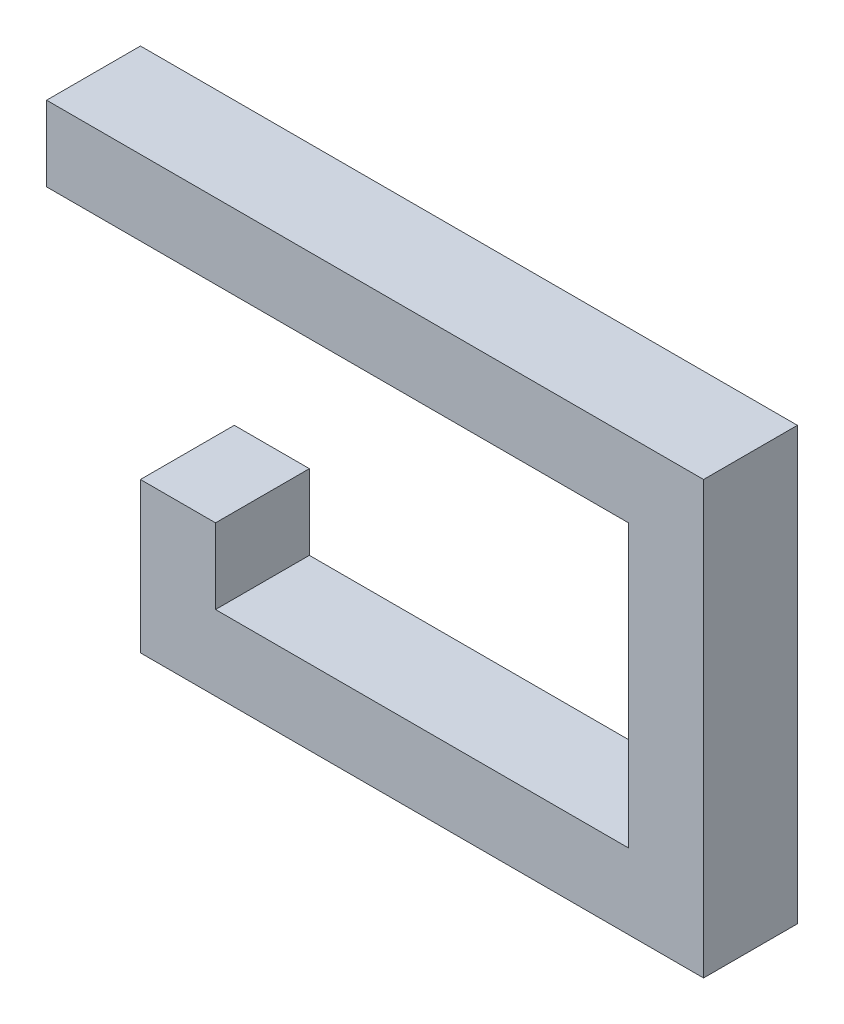
SolidWorks part; units mm, degrees
material "PA Type 6"
ref_plane "Front Plane" through (0, 0, 0) normal (0, 0, 1) x (1, 0, 0)
ref_plane "Top Plane" through (0, 0, 0) normal (0, 1, 0) x (1, 0, 0)
ref_plane "Right Plane" through (0, 0, 0) normal (1, 0, 0) x (0, 0, -1)
sketch "Sketch1" plane through (0, 0, 0) normal (0, 0, 1) x (1, 0, 0)
  line L0 (0, 0) -> (15, 0)
  line L1 (15, 0) -> (15, 11.5)
  line L2 (15, 11.5) -> (-2.5, 11.5)
  line L6 (13, 9.5) -> (13, 2)
  line L8 (0, 2) -> (0, 0)
  line L9 (-2.5, 9.5) -> (13, 9.5)
  line L10 (-2.5, 11.5) -> (-2.5, 9.5)
  line L11 (13, 2) -> (2, 2)
  line L12 (2, 2) -> (2, 4)
  line L13 (2, 4) -> (0, 4)
  line L14 (0, 4) -> (0, 2)
  dimension "D1" = 15
  dimension "D2" = 11.5
  dimension "D3" = 2
  dimension "D4" = 17.5
  dimension "D5" = 2
  dimension "D6" = 2
  dimension "D7" = 2
  dimension "D8" = 2
extrude "Boss-Extrude1" add sketch "Sketch1" along normal blind 2.5
